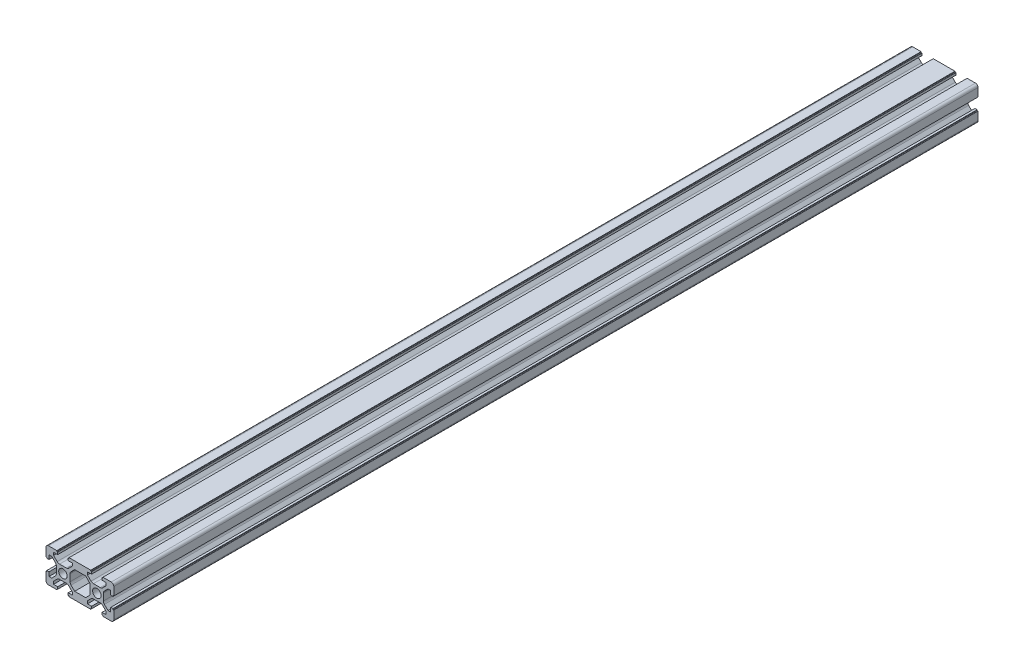
SolidWorks part; units mm, degrees
ref_plane "Спереди" through (0, 0, 0) normal (0, 0, 1) x (1, 0, 0)
ref_plane "Сверху" through (0, 0, 0) normal (0, 1, 0) x (1, 0, 0)
ref_plane "Справа" through (0, 0, 0) normal (1, 0, 0) x (0, 0, -1)
sketch "Sketch1" plane through (0, 0, 0) normal (0, 0, 1) x (1, 0, 0)
  line L0 (0, 10) -> (0, -10) construction
  line L1 (-10, -10) -> (10, -10) construction
  line L2 (-10, -10) -> (-10, 10) construction
  line L3 (-10, 10) -> (10, 10) construction
  line L4 (10, -10) -> (10, 10) construction
  line L5 (-10, -10) -> (10, 10) construction
  line L6 (-10, 10) -> (10, -10) construction
  line L7 (-30, 0) -> (10, 0) construction
  line L8 (0, 3.9) -> (-2.0109, 3.9)
  line L9 (-3.4251, 4.4858) -> (-5.5393, 6.6)
  line L10 (-5.5393, 6.6) -> (-5.5393, 8.2)
  line L11 (-5.5393, 8.2) -> (-3.1, 8.2)
  line L12 (-3.1, 8.2) -> (-3.1, 9.5)
  line L13 (-3.1, 9.5) -> (-3.4, 9.5)
  line L14 (-3.6, 9.7) -> (-3.6, 10)
  line L15 (-3.6, 10) -> (-8.5, 10)
  line L16 (-11.5, 10) -> (-8.5, 10)
  line L17 (-9.7, 3.6) -> (-10, 3.6)
  line L18 (-9.5, 3.1) -> (-9.5, 3.4)
  line L19 (-8.2, 3.1) -> (-9.5, 3.1)
  line L20 (-8.2, 5.5393) -> (-8.2, 3.1)
  line L21 (-6.6, 5.5393) -> (-8.2, 5.5393)
  line L22 (-4.4858, 3.4251) -> (-6.6, 5.5393)
  line L23 (-3.9, 0) -> (-3.9, 2.0109)
  line L24 (3.9, 0) -> (3.9, 2.0109)
  line L25 (4.4858, 3.4251) -> (6.6, 5.5393)
  line L26 (6.6, 5.5393) -> (8.2, 5.5393)
  line L27 (8.2, 5.5393) -> (8.2, 3.1)
  line L28 (8.2, 3.1) -> (9.5, 3.1)
  line L29 (9.5, 3.1) -> (9.5, 3.4)
  line L30 (9.7, 3.6) -> (10, 3.6)
  line L31 (10, 3.6) -> (10, 8.5)
  line L32 (3.6, 10) -> (8.5, 10)
  line L33 (3.6, 9.7) -> (3.6, 10)
  line L34 (3.1, 9.5) -> (3.4, 9.5)
  line L35 (3.1, 8.2) -> (3.1, 9.5)
  line L36 (5.5393, 8.2) -> (3.1, 8.2)
  line L37 (5.5393, 6.6) -> (5.5393, 8.2)
  line L38 (3.4251, 4.4858) -> (5.5393, 6.6)
  line L39 (0, 3.9) -> (2.0109, 3.9)
  line L40 (0, -3.9) -> (2.0109, -3.9)
  line L41 (3.4251, -4.4858) -> (5.5393, -6.6)
  line L42 (5.5393, -6.6) -> (5.5393, -8.2)
  line L43 (5.5393, -8.2) -> (3.1, -8.2)
  line L44 (3.1, -8.2) -> (3.1, -9.5)
  line L45 (3.1, -9.5) -> (3.4, -9.5)
  line L46 (3.6, -9.7) -> (3.6, -10)
  line L47 (3.6, -10) -> (8.5, -10)
  line L48 (10, -3.6) -> (10, -8.5)
  line L49 (9.7, -3.6) -> (10, -3.6)
  line L50 (9.5, -3.1) -> (9.5, -3.4)
  line L51 (8.2, -3.1) -> (9.5, -3.1)
  line L52 (8.2, -5.5393) -> (8.2, -3.1)
  line L53 (6.6, -5.5393) -> (8.2, -5.5393)
  line L54 (4.4858, -3.4251) -> (6.6, -5.5393)
  line L55 (3.9, 0) -> (3.9, -2.0109)
  line L56 (-3.9, 0) -> (-3.9, -2.0109)
  line L57 (-4.4858, -3.4251) -> (-6.6, -5.5393)
  line L58 (-6.6, -5.5393) -> (-8.2, -5.5393)
  line L59 (-8.2, -5.5393) -> (-8.2, -3.1)
  line L60 (-8.2, -3.1) -> (-9.5, -3.1)
  line L61 (-9.5, -3.1) -> (-9.5, -3.4)
  line L62 (-9.7, -3.6) -> (-10, -3.6)
  line L63 (-11.5, -10) -> (-8.5, -10)
  line L64 (-3.6, -10) -> (-8.5, -10)
  line L65 (-3.6, -9.7) -> (-3.6, -10)
  line L66 (-3.1, -9.5) -> (-3.4, -9.5)
  line L67 (-3.1, -8.2) -> (-3.1, -9.5)
  line L68 (-5.5393, -8.2) -> (-3.1, -8.2)
  line L69 (-5.5393, -6.6) -> (-5.5393, -8.2)
  line L70 (-3.4251, -4.4858) -> (-5.5393, -6.6)
  line L71 (0, -3.9) -> (-2.0109, -3.9)
  line L72 (-10, 10) -> (-30, -10) construction
  line L73 (-10, -10) -> (-30, 10) construction
  line L74 (-30, -10) -> (-30, 10) construction
  line L75 (-10, 10) -> (-30, 10) construction
  line L76 (-10, -10) -> (-30, -10) construction
  line L77 (-20, 10) -> (-20, -10) construction
  line L78 (-20, -3.9) -> (-17.9891, -3.9)
  line L79 (-16.5749, -4.4858) -> (-14.4607, -6.6)
  line L80 (-14.4607, -6.6) -> (-14.4607, -8.2)
  line L81 (-14.4607, -8.2) -> (-16.9, -8.2)
  line L82 (-16.9, -8.2) -> (-16.9, -9.5)
  line L83 (-16.9, -9.5) -> (-16.6, -9.5)
  line L84 (-16.4, -9.7) -> (-16.4, -10)
  line L85 (-16.4, -10) -> (-11.5, -10)
  line L86 (-10.2, -3.1) -> (-10.2, -3.4)
  line L87 (-11.5, -3.1) -> (-10.2, -3.1)
  line L88 (-11.5, -5.5393) -> (-11.5, -3.1)
  line L89 (-13.1, -5.5393) -> (-11.5, -5.5393)
  line L90 (-15.2142, -3.4251) -> (-13.1, -5.5393)
  line L91 (-15.8, 0) -> (-15.8, -2.0109)
  line L92 (-23.9, 0) -> (-23.9, -2.0109)
  line L93 (-24.4858, -3.4251) -> (-26.6, -5.5393)
  line L94 (-26.6, -5.5393) -> (-28.2, -5.5393)
  line L95 (-28.2, -5.5393) -> (-28.2, -3.1)
  line L96 (-28.2, -3.1) -> (-29.5, -3.1)
  line L97 (-29.5, -3.1) -> (-29.5, -3.4)
  line L98 (-29.7, -3.6) -> (-30, -3.6)
  line L99 (-30, -3.6) -> (-30, -8.5)
  line L100 (-23.6, -10) -> (-28.5, -10)
  line L101 (-23.6, -9.7) -> (-23.6, -10)
  line L102 (-23.1, -9.5) -> (-23.4, -9.5)
  line L103 (-23.1, -8.2) -> (-23.1, -9.5)
  line L104 (-25.5393, -8.2) -> (-23.1, -8.2)
  line L105 (-25.5393, -6.6) -> (-25.5393, -8.2)
  line L106 (-23.4251, -4.4858) -> (-25.5393, -6.6)
  line L107 (-20, -3.9) -> (-22.0109, -3.9)
  line L108 (-20, 3.9) -> (-22.0109, 3.9)
  line L109 (-23.4251, 4.4858) -> (-25.5393, 6.6)
  line L110 (-25.5393, 6.6) -> (-25.5393, 8.2)
  line L111 (-25.5393, 8.2) -> (-23.1, 8.2)
  line L112 (-23.1, 8.2) -> (-23.1, 9.5)
  line L113 (-23.1, 9.5) -> (-23.4, 9.5)
  line L114 (-23.6, 9.7) -> (-23.6, 10)
  line L115 (-23.6, 10) -> (-28.5, 10)
  line L116 (-30, 3.6) -> (-30, 8.5)
  line L117 (-29.7, 3.6) -> (-30, 3.6)
  line L118 (-29.5, 3.1) -> (-29.5, 3.4)
  line L119 (-28.2, 3.1) -> (-29.5, 3.1)
  line L120 (-28.2, 5.5393) -> (-28.2, 3.1)
  line L121 (-26.6, 5.5393) -> (-28.2, 5.5393)
  line L122 (-24.4858, 3.4251) -> (-26.6, 5.5393)
  line L123 (-23.9, 0) -> (-23.9, 2.0109)
  line L124 (-15.8, 0) -> (-15.8, 2.0109)
  line L125 (-15.2142, 3.4251) -> (-13.1, 5.5393)
  line L126 (-13.1, 5.5393) -> (-11.5, 5.5393)
  line L127 (-11.5, 5.5393) -> (-11.5, 3.1)
  line L128 (-11.5, 3.1) -> (-10.2, 3.1)
  line L129 (-10.2, 3.1) -> (-10.2, 3.4)
  line L130 (-16.4, 10) -> (-11.5, 10)
  line L131 (-16.4, 9.7) -> (-16.4, 10)
  line L132 (-16.9, 9.5) -> (-16.6, 9.5)
  line L133 (-16.9, 8.2) -> (-16.9, 9.5)
  line L134 (-14.4607, 8.2) -> (-16.9, 8.2)
  line L135 (-14.4607, 6.6) -> (-14.4607, 8.2)
  line L136 (-16.5749, 4.4858) -> (-14.4607, 6.6)
  line L137 (-20, 3.9) -> (-17.9891, 3.9)
  line L138 (-10, -3.6) -> (-10, -8.5) [skipped]
  circle A0 centre (0, 0) radius 2.5
  arc A2 (-2.0109, 3.9) -> (-3.4251, 4.4858) centre (-2.0109, 5.9) cw
  arc A3 (-3.4, 9.5) -> (-3.6, 9.7) centre (-3.4, 9.7) cw
  arc A4 (-9.5, 3.4) -> (-9.7, 3.6) centre (-9.7, 3.4) ccw
  arc A5 (-3.9, 2.0109) -> (-4.4858, 3.4251) centre (-5.9, 2.0109) ccw
  arc A6 (10, 8.5) -> (8.5, 10) centre (8.5, 8.5) ccw
  arc A7 (3.9, 2.0109) -> (4.4858, 3.4251) centre (5.9, 2.0109) cw
  arc A8 (9.5, 3.4) -> (9.7, 3.6) centre (9.7, 3.4) cw
  arc A9 (3.4, 9.5) -> (3.6, 9.7) centre (3.4, 9.7) ccw
  arc A10 (2.0109, 3.9) -> (3.4251, 4.4858) centre (2.0109, 5.9) ccw
  arc A11 (8.5, -10) -> (10, -8.5) centre (8.5, -8.5) ccw
  arc A12 (2.0109, -3.9) -> (3.4251, -4.4858) centre (2.0109, -5.9) cw
  arc A13 (3.4, -9.5) -> (3.6, -9.7) centre (3.4, -9.7) cw
  arc A14 (9.5, -3.4) -> (9.7, -3.6) centre (9.7, -3.4) ccw
  arc A15 (3.9, -2.0109) -> (4.4858, -3.4251) centre (5.9, -2.0109) ccw
  arc A17 (-3.9, -2.0109) -> (-4.4858, -3.4251) centre (-5.9, -2.0109) cw
  arc A18 (-9.5, -3.4) -> (-9.7, -3.6) centre (-9.7, -3.4) cw
  arc A19 (-3.4, -9.5) -> (-3.6, -9.7) centre (-3.4, -9.7) ccw
  arc A20 (-2.0109, -3.9) -> (-3.4251, -4.4858) centre (-2.0109, -5.9) ccw
  arc A21 (-17.9891, -3.9) -> (-16.5749, -4.4858) centre (-17.9891, -5.9) cw
  arc A22 (-16.6, -9.5) -> (-16.4, -9.7) centre (-16.6, -9.7) cw
  arc A23 (-10.2, -3.4) -> (-10, -3.6) centre (-10, -3.4) ccw
  arc A24 (-15.8, -2.0109) -> (-15.2142, -3.4251) centre (-13.8, -2.0109) ccw
  arc A26 (-23.9, -2.0109) -> (-24.4858, -3.4251) centre (-25.9, -2.0109) cw
  arc A27 (-29.5, -3.4) -> (-29.7, -3.6) centre (-29.7, -3.4) cw
  arc A28 (-23.4, -9.5) -> (-23.6, -9.7) centre (-23.4, -9.7) ccw
  arc A29 (-22.0109, -3.9) -> (-23.4251, -4.4858) centre (-22.0109, -5.9) ccw
  arc A30 (-28.5, -10) -> (-30, -8.5) centre (-28.5, -8.5) cw
  arc A31 (-22.0109, 3.9) -> (-23.4251, 4.4858) centre (-22.0109, 5.9) cw
  arc A32 (-23.4, 9.5) -> (-23.6, 9.7) centre (-23.4, 9.7) cw
  arc A33 (-29.5, 3.4) -> (-29.7, 3.6) centre (-29.7, 3.4) ccw
  arc A34 (-23.9, 2.0109) -> (-24.4858, 3.4251) centre (-25.9, 2.0109) ccw
  arc A35 (-30, 8.5) -> (-28.5, 10) centre (-28.5, 8.5) cw
  arc A36 (-15.8, 2.0109) -> (-15.2142, 3.4251) centre (-13.8, 2.0109) cw
  arc A37 (-10.2, 3.4) -> (-10, 3.6) centre (-10, 3.4) cw
  arc A38 (-16.6, 9.5) -> (-16.4, 9.7) centre (-16.6, 9.7) ccw
  arc A39 (-17.9891, 3.9) -> (-16.5749, 4.4858) centre (-17.9891, 5.9) ccw
  circle A41 centre (-20, 0) radius 2.5
  point P0 (0, 0)
  point P40 (-10, 0)
  point P42 (0, 0)
  point P70 (0, 0)
  point P98 (0, 0)
  point P126 (0, 0)
  point P227 (-20, 0)
  point P228 (-20, 0)
  point P229 (-20, 0)
  point P230 (-20, 0)
  point P231 (-20, 0)
  dimension "D3" = 5
  dimension "D12" = 2
  dimension "D13" = 0.2
  dimension "D1" = 20
  dimension "D2" = 20
  dimension "D5" = 6.2
  dimension "D6" = 7.2
  dimension "D7" = 1.8
  dimension "D8" = 0.5
  dimension "D9" = 3.4
  dimension "D10" = 1.5
  dimension "D11" = 6.1
  dimension "D14" = 4
extrude "Extrude1" add sketch "Sketch1" along normal blind 510
sketch "Sketch2" plane through (0, 0, 510) normal (0, 0, 1) x (1, 0, 0)
  line L1 (-11.5, 5.5393) -> (-8.2, 5.5393)
  line L2 (-11.5, 5.5393) -> (-11.5, -5.5393)
  line L3 (-11.5, -5.5393) -> (-8.2, -5.5393)
  line L4 (-8.2, 5.5393) -> (-8.2, -5.5393)
extrude "Cut-Extrude1" cut sketch "Sketch2" against normal through all both and the other way through all
